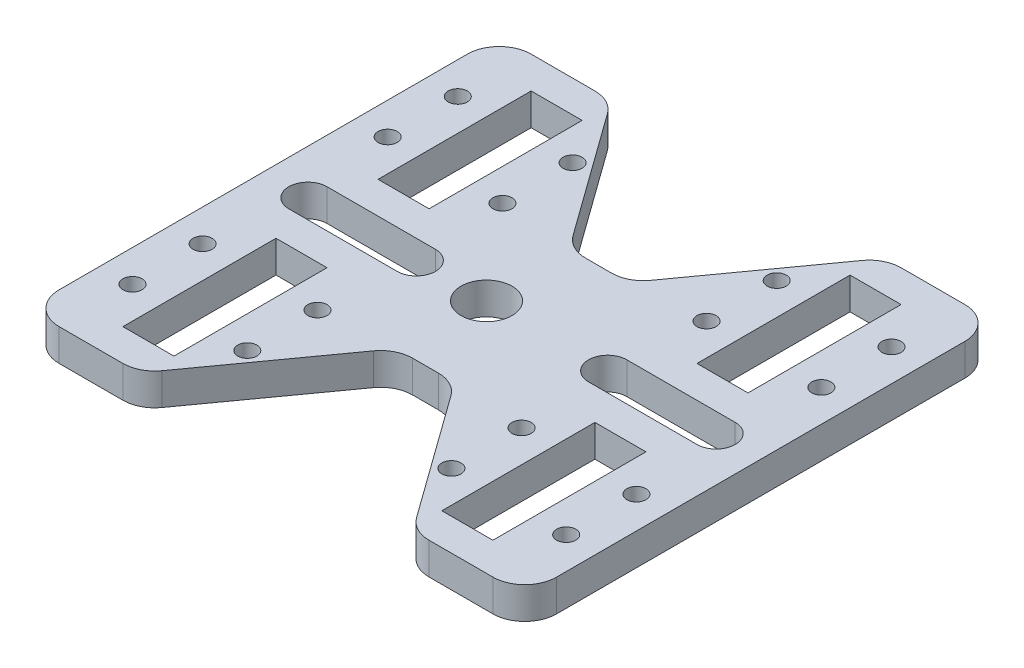
SolidWorks part; units mm, degrees
material "Liga 1060"
ref_plane "Plano frontal" through (0, 0, 0) normal (0, 0, 1) x (1, 0, 0)
ref_plane "Plano superior" through (0, 0, 0) normal (0, 1, 0) x (1, 0, 0)
ref_plane "Plano direito" through (0, 0, 0) normal (1, 0, 0) x (0, 0, -1)
sketch "Esboço1" plane through (0, 0, 0) normal (0, 1, 0) x (1, 0, 0)
  line L0 (0, 0) -> (0, 37) construction
  line L1 (-39, 37) -> (39, 37)
  line L2 (-39, 37) -> (-39, -37)
  line L3 (-39, -37) -> (39, -37)
  line L4 (39, 37) -> (39, -37)
  line L5 (-39, 37) -> (39, -37) construction
  line L6 (-39, -37) -> (39, 37) construction
  line L7 (0, 0) -> (39, 0) construction
  line L8 (29, 8) -> (21, 32) construction
  line L9 (-29, 32) -> (-21, 32)
  line L10 (-29, 32) -> (-29, 8)
  line L11 (-29, 8) -> (-21, 8)
  line L12 (-21, 32) -> (-21, 8)
  line L13 (-29, 32) -> (-21, 8) construction
  line L14 (-29, 8) -> (-21, 32) construction
  line L15 (29, 32) -> (21, 8) construction
  line L16 (21, 32) -> (21, 8)
  line L17 (29, 8) -> (21, 8)
  line L18 (29, 32) -> (29, 8)
  line L19 (29, 32) -> (21, 32)
  line L20 (29, -32) -> (21, -8) construction
  line L21 (-29, -8) -> (-21, -32) construction
  line L22 (-29, -32) -> (-21, -8) construction
  line L23 (29, -8) -> (21, -32) construction
  line L24 (29, -32) -> (21, -32)
  line L25 (29, -32) -> (29, -8)
  line L26 (29, -8) -> (21, -8)
  line L27 (21, -32) -> (21, -8)
  line L28 (-21, -32) -> (-21, -8)
  line L29 (-29, -8) -> (-21, -8)
  line L30 (-29, -32) -> (-29, -8)
  line L31 (-29, -32) -> (-21, -32)
  line L32 (-25, 20) -> (-25, 8) construction
  line L33 (-25, 20) -> (-21, 20) construction
  circle A4 centre (-34, 25.5) radius 1.5
  circle A5 centre (-16, 25.5) radius 1.5
  circle A6 centre (-16, 14.5) radius 1.5
  circle A7 centre (-34, 14.5) radius 1.5
  circle A8 centre (16, 14.5) radius 1.5
  circle A9 centre (16, 25.5) radius 1.5
  circle A10 centre (34, 14.5) radius 1.5
  circle A11 centre (34, 25.5) radius 1.5
  circle A12 centre (34, -14.5) radius 1.5
  circle A13 centre (16, -14.5) radius 1.5
  circle A14 centre (34, -25.5) radius 1.5
  circle A15 centre (16, -25.5) radius 1.5
  circle A16 centre (-16, -14.5) radius 1.5
  circle A17 centre (-16, -25.5) radius 1.5
  circle A18 centre (-34, -14.5) radius 1.5
  circle A19 centre (-34, -25.5) radius 1.5
  point P0 (0, 0)
  point P17 (-25, 20)
  point P26 (25, 20)
  point P35 (25, -20)
  point P36 (-25, -20)
  dimension "D2" = 5
  dimension "D3" = 5
  dimension "D8" = 3
  dimension "D9" = 9
  dimension "D10" = 11
  dimension "D4" = 8
  dimension "D5" = 24
  dimension "D6" = 40
  dimension "D7" = 50
extrude "Ressalto-extrusão1" add sketch "Esboço1" along normal mid plane 5
sketch "Esboço2" plane through (0, 2.5, 0) normal (0, 1, 0) x (1, 0, 0)
  line L0 (-21.4506, -37) -> (-4.5849, -13.572)
  line L1 (-39, -37) -> (39, -37) construction
  line L2 (-4.5849, -13.572) -> (4.5849, -13.572)
  line L3 (0, -13.572) -> (0, 0) construction
  line L4 (21.4506, -37) -> (4.5849, -13.572)
extrude "Corte-extrusão1" cut sketch "Esboço2" against normal through all and the other way through all
mirror "Espelhar1" about plane through (0, 0, 0) normal (0, 0, 1) of "Corte-extrusão1"
sketch "Esboço3" plane through (0, 2.5, 0) normal (0, 1, 0) x (1, 0, 0)
  line L0 (-32, 0) -> (-15, 0) construction
  line L1 (-32, 3) -> (-15, 3)
  line L2 (-32, -3) -> (-15, -3)
  line L3 (-39, 37) -> (-39, -37) construction
  line L4 (0, 0) -> (0, 13.572) construction
  line L5 (-4.5849, 13.572) -> (4.5849, 13.572) construction
  line L6 (32, 0) -> (15, 0) construction
  line L7 (32, 3) -> (15, 3)
  line L8 (32, -3) -> (15, -3)
  line L9 (0, 0) -> (15, 0) construction
  arc A0 (-32, 3) -> (-32, -3) centre (-32, 0) ccw
  arc A1 (-15, -3) -> (-15, 3) centre (-15, 0) ccw
  arc A2 (32, 3) -> (32, -3) centre (32, 0) cw
  arc A3 (15, -3) -> (15, 3) centre (15, 0) cw
  circle A4 centre (-15.5, 15.5) radius 1.5 construction
  circle A5 centre (15.5, 15.5) radius 1.5 construction
  circle A6 centre (15.5, -15.5) radius 1.5 construction
  circle A7 centre (-15.5, -15.5) radius 1.5 construction
  circle A8 centre (-4, 0) radius 4
  point P3 (-23.5, 0)
  point P16 (23.5, 0)
  dimension "D2" = 7
  dimension "D3" = 15
  dimension "D4" = 3
  dimension "D5" = 31
  dimension "D6" = 31
  dimension "D7" = 8
  dimension "D8" = 4
  dimension "D1" = 6
extrude "Corte-extrusão2" cut sketch "Esboço3" against normal blind 10
fillet "Filete1" radius 5 12 edges at (39, 0, 37) (-39, 0, 37) (-39, 0, -37) (39, 0, -37) (21.4506, 0, 37) (4.5849, 0, 13.572) (-4.5849, 0, 13.572) (-21.4506, 0, 37) (-4.5849, 0, -13.572) (4.5849, 0, -13.572) (21.4506, 0, -37) (-21.4506, 0, -37)
